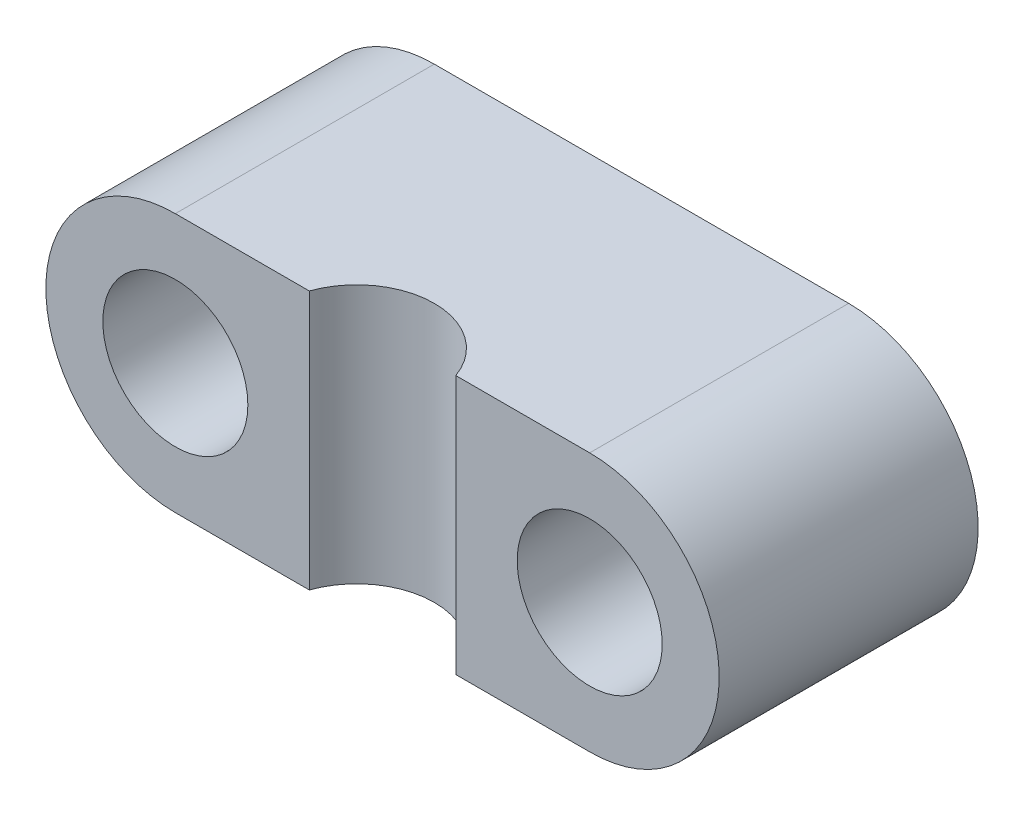
SolidWorks part; units mm, degrees
material "AISI 316 Annealed Stainless Steel Bar (SS)"
ref_plane "Front" through (0, 0, 0) normal (0, 0, 1) x (1, 0, 0)
ref_plane "Top" through (0, 0, 0) normal (0, 1, 0) x (1, 0, 0)
ref_plane "Right" through (0, 0, 0) normal (1, 0, 0) x (0, 0, -1)
sketch "Sketch1" plane through (0, 0, 0) normal (0, 0, 1) x (1, 0, 0)
  line L0 (-4, 0) -> (4, 0) construction
  line L2 (-4, -2.5) -> (4, -2.5)
  line L4 (-4, 2.5) -> (4, 2.5)
  circle A0 centre (-4, 0) radius 1.4
  circle A1 centre (4, 0) radius 1.4
  arc A3 (4, 2.5) -> (4, -2.5) centre (4, 0) cw
  arc A5 (-4, 2.5) -> (-4, -2.5) centre (-4, 0) ccw
  point P4 (0, 0)
  point P5 (0, 0)
  dimension "D2" = 2.8
  dimension "D3" = 2.8
  dimension "D4" = 5
  dimension "D1" = 8
extrude "Boss-Extrude1" add sketch "Sketch1" along normal blind 5
sketch "Sketch2" plane through (0, 2.5, 0) normal (0, 1, 0) x (1, 0, 0)
  line L1 (0, -5.5) -> (0, 0) construction
  line L3 (4, -5) -> (-4, -5) construction
  circle A0 centre (0, -5.5) radius 1.5
  dimension "D2" = 3
  dimension "D1" = 0.5
extrude "Cut-Extrude1" cut sketch "Sketch2" against normal through all
